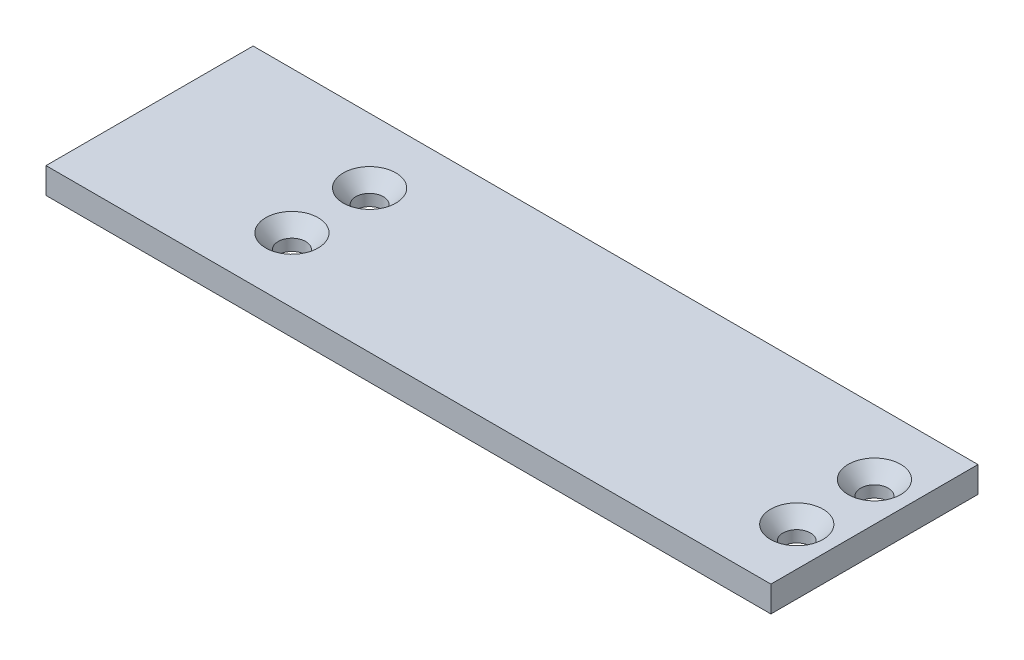
SolidWorks part; units mm, degrees
material "6061 Alloy"
ref_plane "Front Plane" through (0, 0, 0) normal (0, 0, 1) x (1, 0, 0)
ref_plane "Top Plane" through (0, 0, 0) normal (0, 1, 0) x (1, 0, 0)
ref_plane "Right Plane" through (0, 0, 0) normal (1, 0, 0) x (0, 0, -1)
sketch "Sketch1" plane through (0, 0, 0) normal (0, 1, 0) x (1, 0, 0)
  line L1 (88.9, -25.4) -> (-88.9, -25.4)
  line L2 (88.9, -25.4) -> (88.9, 25.4)
  line L3 (88.9, 25.4) -> (-88.9, 25.4)
  line L4 (-88.9, -25.4) -> (-88.9, 25.4)
  line L5 (88.9, -25.4) -> (-88.9, 25.4) construction
  line L6 (88.9, 25.4) -> (-88.9, -25.4) construction
  point P0 (0, 0)
  dimension "D1" = 177.8
  dimension "D2" = 50.8
extrude "Boss-Extrude1" add sketch "Sketch1" along normal mid plane 6.35
hole_wizard "CSK for 1/4 Flat Head Machine Screw1" positions "Sketch2" profile "Sketch3" countersink size "1/4" standard "ANSI Inch"
sketch "Sketch2" plane through (0, 3.175, 0) normal (0, 1, 0) x (1, 0, 0)
  line L0 (-88.9, -25.4) -> (88.9, -25.4) construction
  line L1 (-44.45, -9.525) -> (-44.45, 9.525) construction
  line L3 (88.9, 25.4) -> (-88.9, 25.4) construction
  line L4 (88.9, -25.4) -> (88.9, 25.4) construction
  line L5 (-88.9, 0) -> (88.9, 0) construction
  line L6 (-88.9, 25.4) -> (-88.9, -25.4) construction
  line L8 (79.375, 9.525) -> (79.375, -9.525) construction
  point P2 (-44.45, 9.525)
  point P4 (-44.45, -9.525)
  point P17 (79.375, -9.525)
  point P19 (79.375, 9.525)
  dimension "D1" = 19.05
  dimension "D2" = 15.875
  dimension "D3" = 15.875
  dimension "D4" = 15.875
  dimension "D5" = 133.35
  dimension "D6" = 123.825
sketch "Sketch3" plane through (-44.45, 3.175, -9.525) normal (1, 0, 0) x (0, 0, 1)
  line L0 (0, 0) -> (0, 21.0798)
  line L1 (0, 21.0798) -> (3.3782, 19.05)
  line L2 (3.3782, 19.05) -> (3.3782, 3.5209)
  line L3 (3.3782, 3.5209) -> (6.4389, 0)
  line L5 (6.4389, 0) -> (0, 0)
  line L6 (-3.3782, 3.5209) -> (-6.4389, 0) construction
  line L10 (0, 21.0798) -> (-3.3782, 19.05) construction
  line L11 (0, -6.35) -> (0, 107.95) construction
  dimension "Hole Dia." = 6.7564
  dimension "Hole Depth" = 19.05
  dimension "Near C'Sink Dia." = 12.8778
  dimension "Near C'Sink Angle" = 82
  dimension "Drill Angle" = 118
